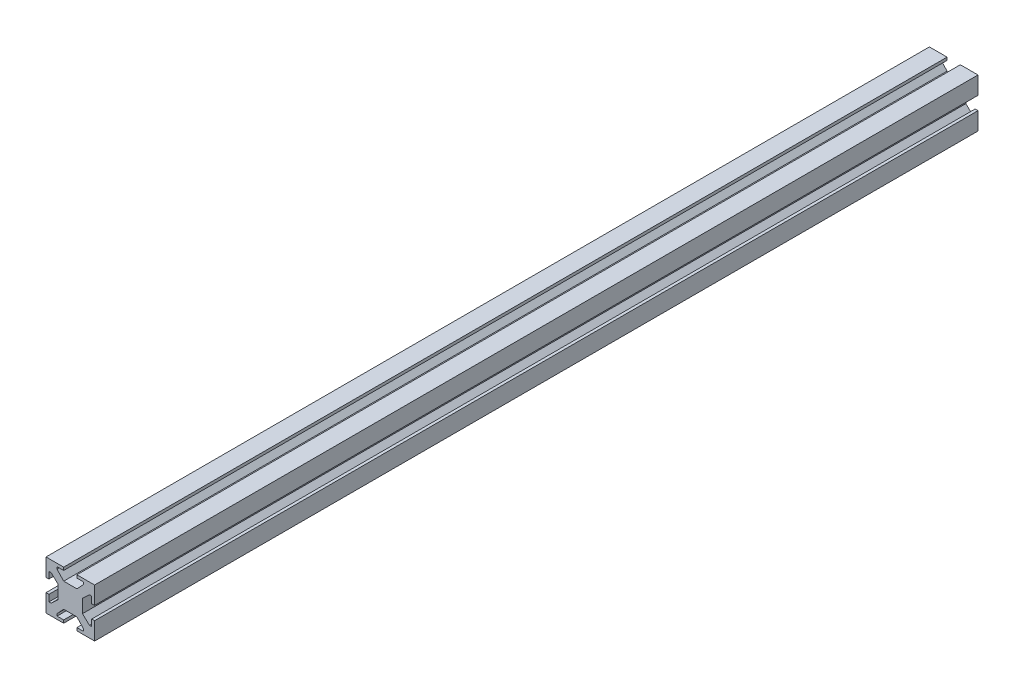
SolidWorks part; units mm, degrees
ref_plane "Front Plane" through (0, 0, 0) normal (0, 0, 1) x (1, 0, 0)
ref_plane "Top Plane" through (0, 0, 0) normal (0, 1, 0) x (1, 0, 0)
ref_plane "Right Plane" through (0, 0, 0) normal (1, 0, 0) x (0, 0, -1)
sketch "Sketch1" plane through (0, 0, 0) normal (0, 0, 1) x (1, 0, 0)
  line L1 (22, 0) -> (14, 0)
  line L2 (22, 0) -> (22, -8)
  line L3 (22, -22) -> (14, -22)
  line L4 (0, 0) -> (0, -8)
  line L6 (20.7, -14) -> (22, -14)
  line L7 (22, -11) -> (16.5, -11) construction
  line L8 (22, -14) -> (22, -22)
  line L9 (22, -8) -> (22, -11) construction
  line L10 (22, -11) -> (22, -14) construction
  line L11 (20.7, -14) -> (20.7, -17)
  line L12 (20.7, -17) -> (19.7, -17)
  line L13 (19.7, -17) -> (16.5, -14)
  line L14 (16.5, -14) -> (16.5, -8)
  line L16 (17, -19.7) -> (14, -16.5)
  line L17 (20.7, -8) -> (22, -8)
  line L18 (20.7, -8) -> (20.7, -5)
  line L19 (20.7, -5) -> (19.7, -5)
  line L20 (19.7, -5) -> (16.5, -8)
  line L21 (0, -11) -> (22, -11) construction
  line L22 (8, -16.5) -> (14, -16.5)
  line L23 (5, -19.7) -> (8, -16.5)
  line L24 (5, -20.7) -> (5, -19.7)
  line L25 (8, -20.7) -> (5, -20.7)
  line L26 (8, -20.7) -> (8, -22)
  line L27 (14, -20.7) -> (14, -22)
  line L28 (14, -20.7) -> (17, -20.7)
  line L29 (17, -20.7) -> (17, -19.7)
  line L30 (2.3, -17) -> (5.5, -14)
  line L31 (5.5, -8) -> (5.5, -14)
  line L32 (2.3, -5) -> (5.5, -8)
  line L33 (1.3, -5) -> (2.3, -5)
  line L34 (1.3, -8) -> (1.3, -5)
  line L35 (1.3, -8) -> (0, -8)
  line L36 (1.3, -14) -> (0, -14)
  line L37 (1.3, -14) -> (1.3, -17)
  line L38 (1.3, -17) -> (2.3, -17)
  line L39 (5, -2.3) -> (8, -5.5)
  line L40 (14, -5.5) -> (8, -5.5)
  line L41 (17, -2.3) -> (14, -5.5)
  line L42 (17, -1.3) -> (17, -2.3)
  line L43 (14, -1.3) -> (17, -1.3)
  line L44 (14, -1.3) -> (14, 0)
  line L45 (8, -1.3) -> (8, 0)
  line L46 (8, -1.3) -> (5, -1.3)
  line L47 (5, -1.3) -> (5, -2.3)
  line L48 (8, 0) -> (0, 0)
  line L49 (14, 0) -> (8, 0) construction
  line L50 (0, -14) -> (0, -22)
  line L51 (0, -8) -> (0, -11) construction
  line L52 (0, -11) -> (0, -14) construction
  line L53 (8, -22) -> (0, -22)
  line L54 (14, -22) -> (8, -22) construction
  point P6 (11, -11)
  point P54 (5.5, -11)
  dimension "D1" = 22
  dimension "D2" = 6
  dimension "D3" = 22
  dimension "D4" = 1.3
  dimension "D5" = 5.5
  dimension "D6" = 6
  dimension "D7" = 1
  dimension "D8" = 3
  dimension "D9" = 4
extrude "Boss-Extrude1" add sketch "Sketch1" along normal blind 400
ref_plane "Plane1" through (0, -11, 0) normal (0, -1, 0) x (-1, 0, 0)
